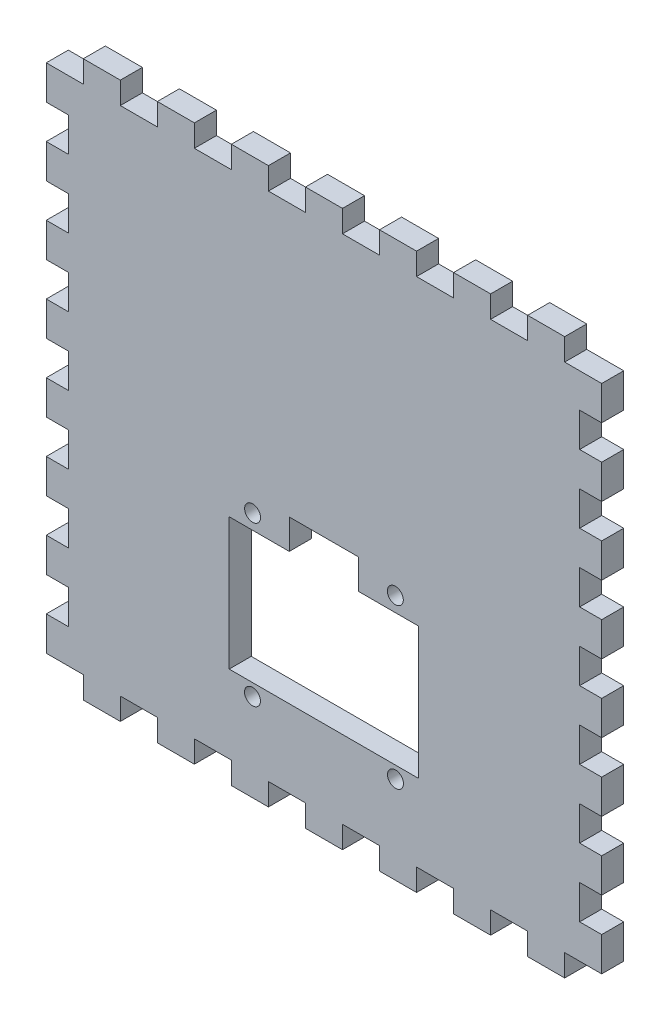
SolidWorks part; units mm, degrees
material "Acrylic (Medium-high impact)"
ref_plane "Front Plane" through (0, 0, 0) normal (0, 0, 1) x (1, 0, 0)
ref_plane "Top Plane" through (0, 0, 0) normal (0, 1, 0) x (1, 0, 0)
ref_plane "Right Plane" through (0, 0, 0) normal (1, 0, 0) x (0, 0, -1)
sketch "Sketch1" plane through (0, 0, 0) normal (0, 0, 1) x (1, 0, 0)
  line L1 (-40, -40) -> (40, -40)
  line L2 (-40, -40) -> (-40, 40)
  line L3 (-40, 40) -> (40, 40)
  line L4 (40, -40) -> (40, 40)
  line L5 (-40, -40) -> (40, 40) construction
  line L6 (-40, 40) -> (40, -40) construction
  point P0 (0, 0)
  dimension "D1" = 80
  dimension "D2" = 80
extrude "Boss-Extrude1" add sketch "Sketch1" along normal blind 3.175
sketch "Sketch3" plane through (0, 0, 3.175) normal (0, 0, 1) x (1, 0, 0)
  line L1 (-34.6667, -36.825) -> (-34.6667, -40)
  line L2 (-40, -36.825) -> (-34.6667, -36.825)
  line L3 (-29.3333, -36.825) -> (-29.3333, -40)
  line L4 (-29.3333, -36.825) -> (-24, -36.825)
  line L5 (-34.6667, -40) -> (-29.3333, -40)
  line L6 (-24, -36.825) -> (-24, -40)
  line L7 (-24, -40) -> (-18.6667, -40)
  line L8 (-18.6667, -36.825) -> (-18.6667, -40)
  line L9 (-18.6667, -36.825) -> (-13.3333, -36.825)
  line L10 (-13.3333, -36.825) -> (-13.3333, -40)
  line L11 (-13.3333, -40) -> (-8, -40)
  line L12 (-8, -36.825) -> (-8, -40)
  line L13 (-8, -36.825) -> (-2.6667, -36.825)
  line L14 (-2.6667, -36.825) -> (-2.6667, -40)
  line L15 (-2.6667, -40) -> (2.6667, -40)
  line L16 (2.6667, -36.825) -> (2.6667, -40)
  line L17 (2.6667, -36.825) -> (8, -36.825)
  line L18 (8, -36.825) -> (8, -40)
  line L19 (8, -40) -> (13.3333, -40)
  line L20 (13.3333, -36.825) -> (13.3333, -40)
  line L21 (13.3333, -36.825) -> (18.6667, -36.825)
  line L22 (18.6667, -36.825) -> (18.6667, -40)
  line L23 (18.6667, -40) -> (24, -40)
  line L24 (24, -36.825) -> (24, -40)
  line L25 (24, -36.825) -> (29.3333, -36.825)
  line L26 (29.3333, -36.825) -> (29.3333, -40)
  line L27 (29.3333, -40) -> (34.6667, -40)
  line L28 (34.6667, -40) -> (34.6667, -36.825)
  line L29 (34.6667, -36.825) -> (40, -36.825)
  line L31 (0, 0) -> (50000, 0) construction
  line L32 (34.6667, 36.825) -> (40, 36.825)
  line L33 (40, -40) -> (40, 40) construction
  line L34 (34.6667, 40) -> (34.6667, 36.825)
  line L35 (29.3333, 40) -> (34.6667, 40)
  line L36 (29.3333, 36.825) -> (29.3333, 40)
  line L37 (24, 36.825) -> (29.3333, 36.825)
  line L38 (24, 36.825) -> (24, 40)
  line L39 (18.6667, 40) -> (24, 40)
  line L40 (18.6667, 36.825) -> (18.6667, 40)
  line L41 (13.3333, 36.825) -> (18.6667, 36.825)
  line L42 (13.3333, 36.825) -> (13.3333, 40)
  line L43 (8, 40) -> (13.3333, 40)
  line L44 (8, 36.825) -> (8, 40)
  line L45 (2.6667, 36.825) -> (8, 36.825)
  line L46 (2.6667, 36.825) -> (2.6667, 40)
  line L47 (-2.6667, 40) -> (2.6667, 40)
  line L48 (-2.6667, 36.825) -> (-2.6667, 40)
  line L49 (-8, 36.825) -> (-2.6667, 36.825)
  line L50 (-8, 36.825) -> (-8, 40)
  line L51 (-13.3333, 40) -> (-8, 40)
  line L52 (-13.3333, 36.825) -> (-13.3333, 40)
  line L53 (-18.6667, 36.825) -> (-13.3333, 36.825)
  line L54 (-18.6667, 36.825) -> (-18.6667, 40)
  line L55 (-24, 40) -> (-18.6667, 40)
  line L56 (-24, 36.825) -> (-24, 40)
  line L57 (-34.6667, 40) -> (-29.3333, 40)
  line L58 (-29.3333, 36.825) -> (-24, 36.825)
  line L59 (-29.3333, 36.825) -> (-29.3333, 40)
  line L60 (-40, 36.825) -> (-34.6667, 36.825)
  line L61 (-34.6667, 36.825) -> (-34.6667, 40)
  line L64 (40, 27.005) -> (40, 22.095)
  line L65 (40, 31.915) -> (36.825, 31.915)
  line L66 (36.825, 31.915) -> (36.825, 27.005)
  line L67 (36.825, 27.005) -> (40, 27.005)
  line L69 (40, 22.095) -> (36.825, 22.095)
  line L70 (36.825, 22.095) -> (36.825, 17.185)
  line L71 (36.825, 17.185) -> (40, 17.185)
  line L72 (40, 17.185) -> (40, 12.275)
  line L73 (40, 12.275) -> (36.825, 12.275)
  line L74 (36.825, 12.275) -> (36.825, 7.365)
  line L75 (36.825, 7.365) -> (40, 7.365)
  line L76 (40, 7.365) -> (40, 2.455)
  line L77 (40, 2.455) -> (36.825, 2.455)
  line L78 (36.825, 2.455) -> (36.825, -2.455)
  line L79 (36.825, -2.455) -> (40, -2.455)
  line L80 (40, -2.455) -> (40, -7.365)
  line L81 (40, -7.365) -> (36.825, -7.365)
  line L82 (36.825, -7.365) -> (36.825, -12.275)
  line L83 (36.825, -12.275) -> (40, -12.275)
  line L84 (40, -12.275) -> (40, -17.185)
  line L85 (40, -17.185) -> (36.825, -17.185)
  line L86 (36.825, -17.185) -> (36.825, -22.095)
  line L87 (36.825, -22.095) -> (40, -22.095)
  line L88 (40, -22.095) -> (40, -27.005)
  line L89 (40, -27.005) -> (36.825, -27.005)
  line L90 (36.825, -27.005) -> (36.825, -31.915)
  line L91 (36.825, -31.915) -> (40, -31.915)
  line L92 (40, -31.915) -> (40, -36.825)
  line L93 (0, 0) -> (0, 50000) construction
  line L94 (0, 0) -> (-50000, 0) construction
  line L95 (-40, -31.915) -> (-40, -36.825)
  line L96 (-36.825, -31.915) -> (-40, -31.915)
  line L97 (-36.825, -27.005) -> (-36.825, -31.915)
  line L98 (-40, -27.005) -> (-36.825, -27.005)
  line L99 (-40, -22.095) -> (-40, -27.005)
  line L100 (-36.825, -22.095) -> (-40, -22.095)
  line L101 (-36.825, -17.185) -> (-36.825, -22.095)
  line L102 (-40, -17.185) -> (-36.825, -17.185)
  line L103 (-40, -12.275) -> (-40, -17.185)
  line L104 (-36.825, -12.275) -> (-40, -12.275)
  line L105 (-36.825, -7.365) -> (-36.825, -12.275)
  line L106 (-40, -7.365) -> (-36.825, -7.365)
  line L107 (-40, -2.455) -> (-40, -7.365)
  line L108 (-36.825, -2.455) -> (-40, -2.455)
  line L109 (-36.825, 2.455) -> (-36.825, -2.455)
  line L110 (-40, 2.455) -> (-36.825, 2.455)
  line L111 (-40, 7.365) -> (-40, 2.455)
  line L112 (-36.825, 7.365) -> (-40, 7.365)
  line L113 (-36.825, 12.275) -> (-36.825, 7.365)
  line L114 (-40, 12.275) -> (-36.825, 12.275)
  line L115 (-40, 17.185) -> (-40, 12.275)
  line L116 (-36.825, 17.185) -> (-40, 17.185)
  line L117 (-36.825, 22.095) -> (-36.825, 17.185)
  line L118 (-40, 22.095) -> (-36.825, 22.095)
  line L119 (-40, 36.825) -> (-40, 31.915)
  line L120 (-36.825, 27.005) -> (-40, 27.005)
  line L121 (-36.825, 31.915) -> (-36.825, 27.005)
  line L122 (-40, 31.915) -> (-36.825, 31.915)
  line L123 (-40, 27.005) -> (-40, 22.095)
extrude "Cut-Extrude2" cut sketch "Sketch3" against normal through all and the other way through all
sketch "Sketch4" plane through (0, 0, 3.175) normal (0, 0, 1) x (1, 0, 0)
  line L0 (0, 0) -> (0, -50000) construction
  line L1 (-2.6667, -36.825) -> (-8, -36.825) construction
  line L2 (-13.65, -29.325) -> (13.65, -29.325) construction
  line L3 (-13.65, -29.325) -> (-13.65, -2.325) construction
  line L4 (-13.65, -2.325) -> (13.65, -2.325) construction
  line L5 (13.65, -29.325) -> (13.65, -2.325) construction
  line L6 (-13.65, -29.325) -> (13.65, -2.325) construction
  line L7 (-13.65, -2.325) -> (13.65, -29.325) construction
  line L8 (5, -2.325) -> (5, -6.625)
  line L9 (5, -6.625) -> (13.65, -6.625)
  line L10 (13.65, -6.625) -> (13.65, -25.625)
  line L11 (13.65, -25.625) -> (-13.65, -25.625)
  line L12 (-13.65, -6.625) -> (-13.65, -25.625)
  line L13 (-5, -6.625) -> (-13.65, -6.625)
  line L14 (-5, -2.325) -> (-5, -6.625)
  line L15 (-5, -2.325) -> (5, -2.325)
  circle A0 centre (-10.28, -4.475) radius 1.15
  circle A1 centre (-10.3, -27.375) radius 1.15
  circle A2 centre (10.3, -27.375) radius 1.15
  circle A3 centre (10.28, -4.475) radius 1.15
  point P3 (0, -15.825)
  point P14 (5, -4.475)
  point P17 (0, -25.625)
  point P26 (-11.7503, -29.325)
  point P27 (-11.9581, -30.646)
  dimension "D7" = 3.37
  dimension "D1" = 27
  dimension "D2" = 27.3
  dimension "D3" = 7.5
  dimension "D4" = 10
  dimension "D5" = 19
  dimension "D6" = 22.7
  dimension "D8" = 2.15
  dimension "D9" = 3.35
  dimension "D10" = 1.95
extrude "Cut-Extrude3" cut sketch "Sketch4" against normal through all
